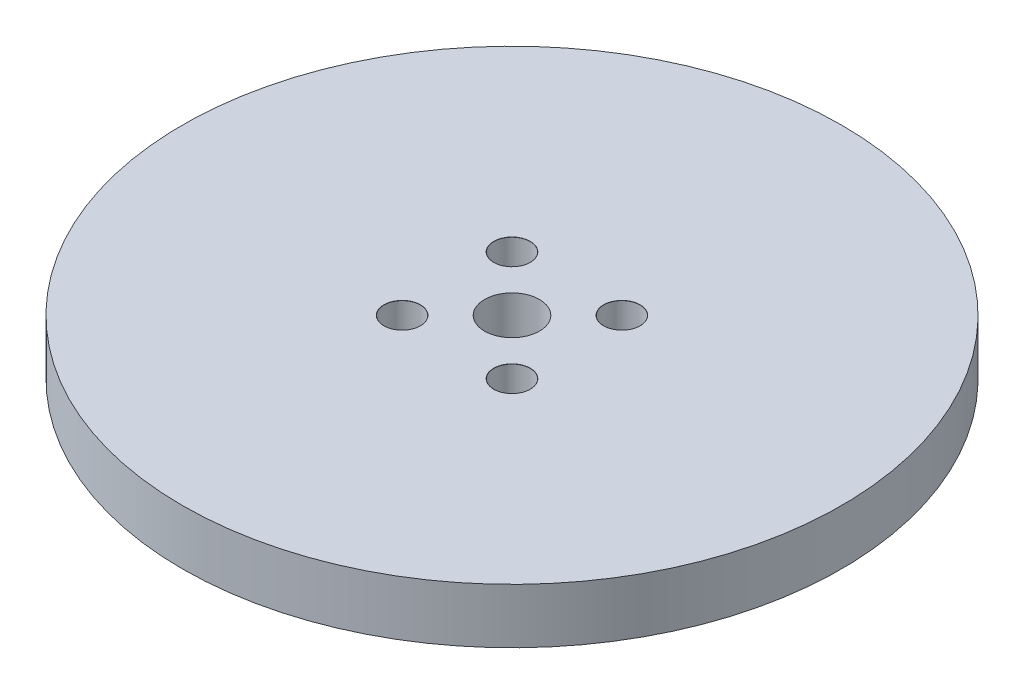
SolidWorks part; units mm, degrees
ref_plane "Front Plane" through (0, 0, 0) normal (0, 0, 1) x (1, 0, 0)
ref_plane "Top Plane" through (0, 0, 0) normal (0, 1, 0) x (1, 0, 0)
ref_plane "Right Plane" through (0, 0, 0) normal (1, 0, 0) x (0, 0, -1)
sketch "Sketch1" plane through (0, 0, 0) normal (0, 1, 0) x (1, 0, 0)
  circle A0 centre (0, 0) radius 60
  circle A1 centre (0, 0) radius 5
  dimension "D1" = 120
  dimension "D2" = 10
extrude "Boss-Extrude1" add sketch "Sketch1" along normal blind 10
hole_wizard "M6 Clearance Hole1" positions "Sketch2" profile "Sketch3" hole size "M6" standard "ANSI Metric" end condition through all
sketch "Sketch2" plane through (0, 10, 0) normal (0, 1, 0) x (1, 0, 0)
  line L0 (-10, 10) -> (-10, -10) construction
  line L1 (-10, -10) -> (10, -10) construction
  line L2 (10, -10) -> (10, 10) construction
  line L3 (10, 10) -> (-10, 10) construction
  point P0 (-10, 10)
  point P2 (10, 10)
  point P4 (-10, -10)
  point P6 (10, -10)
  point P15 (10, 0)
  point P16 (0, -10)
  dimension "D1" = 20
sketch "Sketch3" plane through (-10, 10, -10) normal (1, 0, 0) x (0, 0, 1)
  line L0 (0, 0) -> (0, 10)
  line L1 (0, 10) -> (3.3, 10)
  line L2 (3.3, 10) -> (3.3, 0.021)
  line L3 (3.3, 0.021) -> (3.325, 0)
  line L5 (3.325, 0) -> (0, 0)
  line L6 (-3.3, 0.021) -> (-3.325, 0) construction
  line L11 (0, -6.35) -> (0, 107.95) construction
  dimension "Thru Hole Dia." = 6.6
  dimension "Thru Hole Depth" = 10
  dimension "Near C'Sink Dia." = 6.65
  dimension "Near C'Sink Angle" = 100
